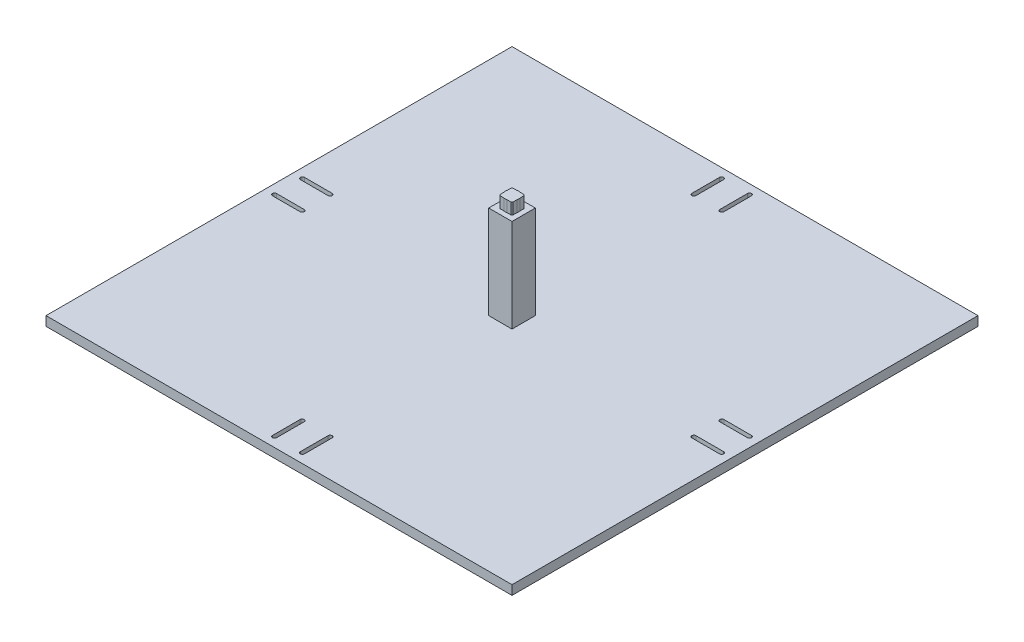
SolidWorks part; units mm, degrees
ref_plane "Plano frontal" through (0, 0, 0) normal (0, 0, 1) x (1, 0, 0)
ref_plane "Plano superior" through (0, 0, 0) normal (0, 1, 0) x (1, 0, 0)
ref_plane "Plano direito" through (0, 0, 0) normal (1, 0, 0) x (0, 0, -1)
sketch "Esboço1" plane through (0, 0, 0) normal (0, 1, 0) x (1, 0, 0)
  line L1 (0, 0) -> (500, 0)
  line L2 (0, 0) -> (0, 500)
  line L3 (0, 500) -> (500, 500)
  line L4 (500, 0) -> (500, 500)
  dimension "D1" = 500
extrude "Ressalto-extrusão1" add sketch "Esboço1" along normal blind 10
sketch "Esboço2" plane through (0, 10, 0) normal (0, 1, 0) x (1, 0, 0)
  line L0 (500, 500) -> (0, 500) construction
  line L1 (232.85, 489.85) -> (232.85, 460.15)
  line L2 (237.15, 489.85) -> (237.15, 460.15)
  line L3 (262.85, 489.85) -> (262.85, 460.15)
  line L4 (267.15, 489.85) -> (267.15, 460.15)
  line L29 (489.85, 267.15) -> (460.15, 267.15)
  line L30 (489.85, 262.85) -> (460.15, 262.85)
  line L31 (489.85, 237.15) -> (460.15, 237.15)
  line L32 (489.85, 232.85) -> (460.15, 232.85)
  line L33 (267.15, 10.15) -> (267.15, 39.85)
  line L34 (262.85, 10.15) -> (262.85, 39.85)
  line L35 (237.15, 10.15) -> (237.15, 39.85)
  line L36 (232.85, 10.15) -> (232.85, 39.85)
  line L37 (10.15, 232.85) -> (39.85, 232.85)
  line L38 (10.15, 237.15) -> (39.85, 237.15)
  line L39 (10.15, 262.85) -> (39.85, 262.85)
  line L40 (10.15, 267.15) -> (39.85, 267.15)
  arc A0 (237.15, 489.85) -> (232.85, 489.85) centre (235, 489.85) ccw
  arc A1 (232.85, 460.15) -> (237.15, 460.15) centre (235, 460.15) ccw
  arc A2 (267.15, 489.85) -> (262.85, 489.85) centre (265, 489.85) ccw
  arc A3 (262.85, 460.15) -> (267.15, 460.15) centre (265, 460.15) ccw
  arc A20 (489.85, 262.85) -> (489.85, 267.15) centre (489.85, 265) ccw
  arc A21 (460.15, 267.15) -> (460.15, 262.85) centre (460.15, 265) ccw
  arc A22 (489.85, 232.85) -> (489.85, 237.15) centre (489.85, 235) ccw
  arc A23 (460.15, 237.15) -> (460.15, 232.85) centre (460.15, 235) ccw
  arc A24 (262.85, 10.15) -> (267.15, 10.15) centre (265, 10.15) ccw
  arc A25 (267.15, 39.85) -> (262.85, 39.85) centre (265, 39.85) ccw
  arc A26 (232.85, 10.15) -> (237.15, 10.15) centre (235, 10.15) ccw
  arc A27 (237.15, 39.85) -> (232.85, 39.85) centre (235, 39.85) ccw
  arc A28 (10.15, 237.15) -> (10.15, 232.85) centre (10.15, 235) ccw
  arc A29 (39.85, 232.85) -> (39.85, 237.15) centre (39.85, 235) ccw
  arc A30 (10.15, 267.15) -> (10.15, 262.85) centre (10.15, 265) ccw
  arc A31 (39.85, 262.85) -> (39.85, 267.15) centre (39.85, 265) ccw
  point P17 (250, 500)
  point P64 (250, 250)
  dimension "D1" = 4.3
  dimension "D3" = 4.3
  dimension "D2" = 10.15
  dimension "D4" = 29.7
  dimension "D5" = 30
  dimension "D6" = 15
  dimension "D7" = 4
extrude "Corte-extrusão2" cut sketch "Esboço2" against normal through all both
sketch "Esboço3" plane through (0, 10, 0) normal (0, 1, 0) x (1, 0, 0)
  line L0 (0, 250) -> (500, 250) construction
  line L1 (0, 500) -> (0, 0) construction
  line L2 (500, 0) -> (500, 500) construction
  line L3 (250, 500) -> (250, 0) construction
  line L4 (500, 500) -> (0, 500) construction
  line L5 (0, 0) -> (500, 0) construction
  line L7 (237.5, 262.5) -> (262.5, 262.5)
  line L8 (237.5, 262.5) -> (237.5, 237.5)
  line L9 (237.5, 237.5) -> (262.5, 237.5)
  line L10 (262.5, 262.5) -> (262.5, 237.5)
  dimension "D1" = 25
  dimension "D2" = 25
  dimension "D3" = 12.5
  dimension "D4" = 12.5
extrude "Ressalto-extrusão2" add sketch "Esboço3" along normal blind 100
sketch "Esboço4" plane through (0, 110, 0) normal (0, 1, 0) x (1, 0, 0)
  line L0 (237.5, 250) -> (262.5, 250) construction
  line L1 (237.5, 262.5) -> (237.5, 237.5) construction
  line L2 (262.5, 237.5) -> (262.5, 262.5) construction
  line L3 (250, 262.5) -> (250, 237.5) construction
  line L4 (262.5, 262.5) -> (237.5, 262.5) construction
  line L5 (237.5, 237.5) -> (262.5, 237.5) construction
  line L7 (243, 257) -> (257, 257)
  line L8 (243, 257) -> (243, 243)
  line L9 (243, 243) -> (257, 243)
  line L10 (257, 257) -> (257, 243)
  dimension "D1" = 14
  dimension "D2" = 14
  dimension "D3" = 7
  dimension "D4" = 7
extrude "Ressalto-extrusão3" add sketch "Esboço4" along normal blind 12
sketch "Esboço5" plane through (0, 122, 0) normal (0, 1, 0) x (1, 0, 0)
  line L0 (243, 250) -> (257, 250) construction
  line L1 (243, 257) -> (243, 243) construction
  line L2 (257, 243) -> (257, 257) construction
  line L3 (250, 257) -> (250, 243) construction
  line L4 (257, 257) -> (243, 257) construction
  line L5 (243, 243) -> (257, 243) construction
  circle A0 centre (250, 250) radius 7.24
  dimension "D1" = 14.48
extrude "Ressalto-extrusão4" add sketch "Esboço5" against normal up to surface (12 mm away) up to face at (250, 110, -250)
chamfer "Chanfro1" distance 1 4 edges at (257, 116, -257) (257, 116, -243) (243, 116, -243) (243, 116, -257)
